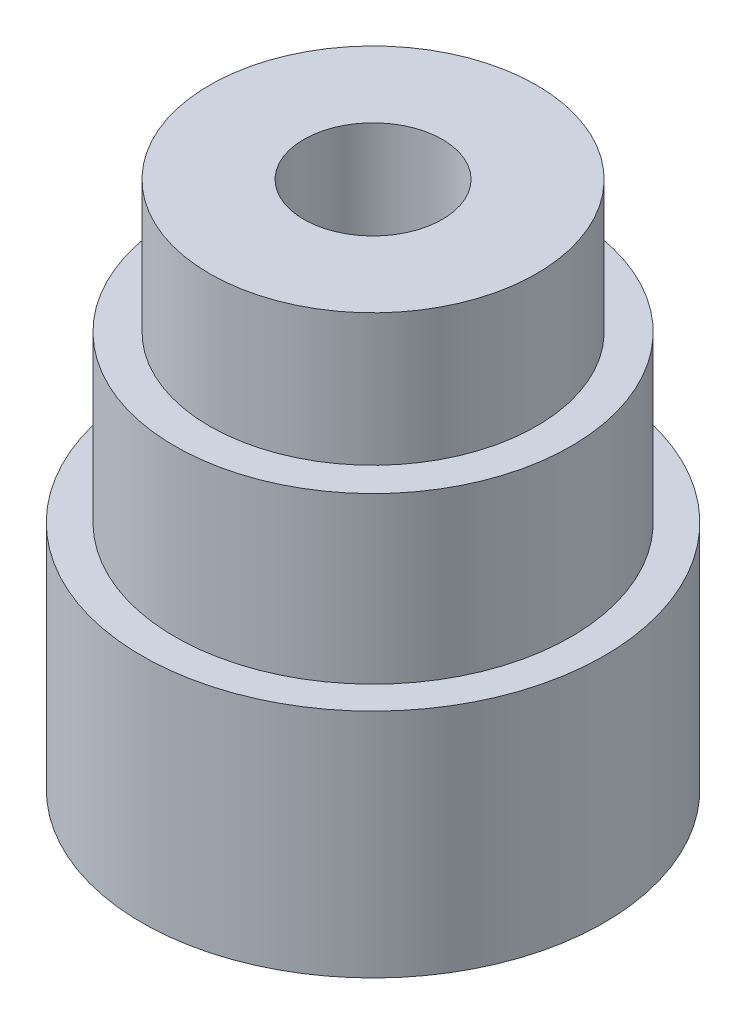
SolidWorks part; units mm, degrees
ref_plane "前视基准面" through (0, 0, 0) normal (0, 0, 1) x (1, 0, 0)
ref_plane "上视基准面" through (0, 0, 0) normal (0, 1, 0) x (1, 0, 0)
ref_plane "右视基准面" through (0, 0, 0) normal (1, 0, 0) x (0, 0, -1)
sketch "草图1" plane through (0, 0, 0) normal (0, 0, 1) x (1, 0, 0)
  line L0 (0, 0) -> (0, 16)
  line L1 (0, 16) -> (-4.95, 16)
  line L2 (-4.95, 16) -> (-4.95, 12)
  line L3 (-4.95, 12) -> (-6, 12)
  line L4 (-6, 12) -> (-6, 7)
  line L5 (-6, 7) -> (-7, 7)
  line L6 (-7, 7) -> (-7, 0)
  line L7 (-7, 0) -> (0, 0)
  dimension "D1" = 7
  dimension "D2" = 6
  dimension "D3" = 4.95
  dimension "D4" = 4
  dimension "D5" = 5
  dimension "D6" = 7
revolve "旋转1" add sketch "草图1" angle 360 about L0
sketch "草图2" plane through (0, 16, 0) normal (0, 1, 0) x (1, 0, 0)
  circle A0 centre (0, 0) radius 2.1
  dimension "D1" = 4.2
extrude "切除-拉伸1" cut sketch "草图2" against normal blind 19
